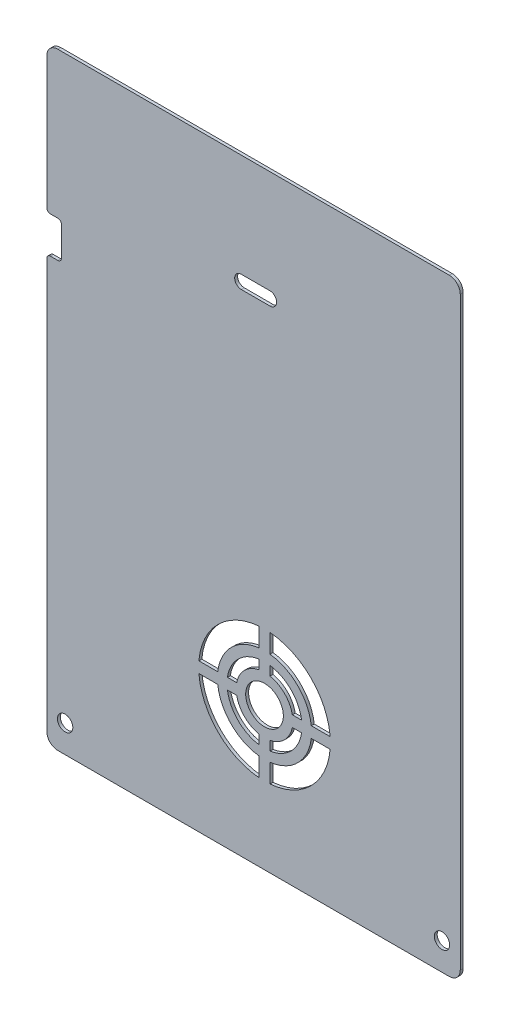
SolidWorks part; units mm, degrees
material "3.0205 (EN-AW 1200)"
ref_plane "Alzado" through (0, 0, 0) normal (0, 0, 1) x (1, 0, 0)
ref_plane "Planta" through (0, 0, 0) normal (0, 1, 0) x (1, 0, 0)
ref_plane "Vista lateral" through (0, 0, 0) normal (1, 0, 0) x (0, 0, -1)
sketch "Croquis1" plane through (0, 0, 0) normal (0, 0, 1) x (1, 0, 0)
  line L27 (-55.5, 86) -> (-55.5, 78)
  line L28 (-56.5, 127) -> (50.5, 127)
  line L36 (-59.5, 124) -> (-59.5, 88)
  line L62 (-56.5, -39) -> (50.5, -39)
  line L63 (53.5, 124) -> (53.5, -36)
  line L64 (-56.5, 87) -> (-58.5, 87)
  line L65 (-56.5, 77) -> (-58.5, 77)
  line L66 (-59.5, 76) -> (-59.5, -36)
  arc A64 (50.5, -39) -> (53.5, -36) centre (50.5, -36) ccw
  arc A65 (-59.5, -36) -> (-56.5, -39) centre (-56.5, -36) ccw
  arc A66 (50.5, 127) -> (53.5, 124) centre (50.5, 124) cw
  arc A67 (-56.5, 127) -> (-59.5, 124) centre (-56.5, 124) ccw
  arc A68 (-55.5, 86) -> (-56.5, 87) centre (-56.5, 86) ccw
  arc A69 (-55.5, 78) -> (-56.5, 77) centre (-56.5, 78) cw
  arc A70 (-58.5, 77) -> (-59.5, 76) centre (-58.5, 76) ccw
  arc A71 (-58.5, 87) -> (-59.5, 88) centre (-58.5, 88) cw
  point P63 (53.5, -39)
  point P66 (-59.5, -39)
  point P69 (53.5, 127)
  point P76 (-55.5, 87)
  point P79 (-55.5, 77)
  point P82 (-59.5, 77)
  dimension "D3" = 3
  dimension "D8" = 113
  dimension "D4" = 1
  dimension "D9" = 166
  dimension "D15" = 109
  dimension "D16" = 40
  dimension "D17" = 116
extrude "Saliente-Extruir1" add sketch "Croquis1" along normal blind 0.8
sketch "Croquis4" plane through (0, 0, 0.8) normal (0, 0, 1) x (1, 0, 0)
  line L67 (-6.3489, 98.8) -> (1.5, 98.8)
  line L68 (-6.3489, 95.2) -> (1.5, 95.2)
  circle A55 centre (-54.5, -31.5) radius 2.1
  circle A56 centre (48.5, -31.5) radius 2.1
  arc A57 (-6.3489, 98.8) -> (-6.3489, 95.2) centre (-6.3489, 97) ccw
  arc A58 (1.5, 95.2) -> (1.5, 98.8) centre (1.5, 97) ccw
  dimension "D10" = 4.2
  dimension "D18" = 3.6
sketch "Croquis5" plane through (0, 0, 0.8) normal (0, 0, 1) x (1, 0, 0)
  line L0 (-17.9374, -1.5) -> (-12.7873, -1.5)
  line L1 (-17.9374, 1.5) -> (-12.7873, 1.5)
  line L2 (-1.5, 17.9374) -> (-1.5, 12.7873)
  line L3 (1.5, -17.9374) -> (1.5, -12.7873)
  line L4 (-10.1396, 1.5) -> (-7.6035, 1.5)
  line L5 (-10.1396, -1.5) -> (-7.6035, -1.5)
  line L6 (-1.5, -7.6035) -> (-1.5, -10.1396)
  line L7 (-1.5, -12.7873) -> (-1.5, -17.9374)
  line L8 (7.6035, -1.5) -> (10.1396, -1.5)
  line L9 (7.6035, 1.5) -> (10.1396, 1.5)
  line L10 (1.5, 7.6035) -> (1.5, 10.1396)
  line L11 (1.5, -10.1396) -> (1.5, -7.6035)
  line L12 (12.7873, -1.5) -> (17.9374, -1.5)
  line L13 (12.7873, 1.5) -> (17.9374, 1.5)
  line L14 (1.5, 12.7873) -> (1.5, 17.9374)
  line L15 (-1.5, 10.1396) -> (-1.5, 7.6035)
  circle A0 centre (0, 0) radius 5.15
  arc A1 (-7.6035, -1.5) -> (-1.5, -7.6035) centre (0, 0) ccw
  arc A2 (-10.1396, -1.5) -> (-1.5, -10.1396) centre (0, 0) ccw
  arc A3 (-12.7873, -1.5) -> (-1.5, -12.7873) centre (0, 0) ccw
  arc A4 (17.9374, 1.5) -> (1.5, 17.9374) centre (0, 0) ccw
  arc A5 (7.6035, 1.5) -> (1.5, 7.6035) centre (0, 0) ccw
  arc A6 (10.1396, 1.5) -> (1.5, 10.1396) centre (0, 0) ccw
  arc A7 (12.7873, 1.5) -> (1.5, 12.7873) centre (0, 0) ccw
  arc A8 (1.5, -7.6035) -> (7.6035, -1.5) centre (0, 0) ccw
  arc A9 (1.5, -10.1396) -> (10.1396, -1.5) centre (0, 0) ccw
  arc A10 (1.5, -12.7873) -> (12.7873, -1.5) centre (0, 0) ccw
  arc A11 (1.5, -17.9374) -> (17.9374, -1.5) centre (0, 0) ccw
  arc A12 (-1.5, 7.6035) -> (-7.6035, 1.5) centre (0, 0) ccw
  arc A13 (-1.5, 10.1396) -> (-10.1396, 1.5) centre (0, 0) ccw
  arc A14 (-1.5, 12.7873) -> (-12.7873, 1.5) centre (0, 0) ccw
  arc A15 (-1.5, 17.9374) -> (-17.9374, 1.5) centre (0, 0) ccw
  arc A16 (-17.9374, -1.5) -> (-1.5, -17.9374) centre (0, 0) ccw
extrude "Cortar-Extruir1" cut sketch "Croquis5" against normal blind 0.8
extrude "Cortar-Extruir2" cut sketch "Croquis4" against normal blind 0.8
